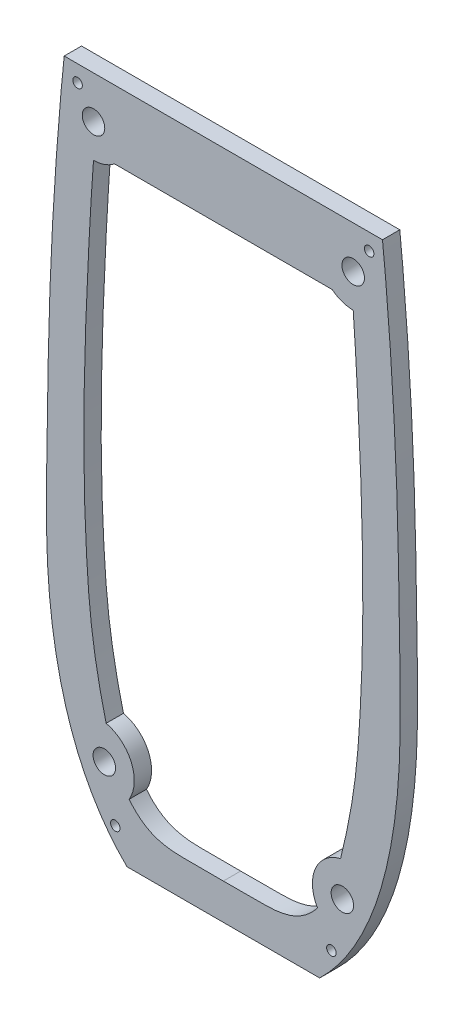
SolidWorks part; units mm, degrees
ref_plane "Front Plane" through (0, 0, 0) normal (0, 0, 1) x (1, 0, 0)
ref_plane "Top Plane" through (0, 0, 0) normal (0, 1, 0) x (1, 0, 0)
ref_plane "Right Plane" through (0, 0, 0) normal (1, 0, 0) x (0, 0, -1)
sketch "Sketch1" plane through (0, 0, 0) normal (0, 0, 1) x (1, 0, 0)
  line L5 (0, 5.6921) -> (0, 13.9608)
  line L6 (0, 5.6921) -> (-22.2594, 5.6921)
  line L7 (-36.7676, 160.6704) -> (0, 160.6704)
  line L8 (0, 160.6704) -> (0, 144.8979)
  line L9 (0, 144.8979) -> (-25.1616, 144.8979)
  circle A0 centre (-27.5, 24.0877) radius 2.6
  circle A1 centre (-30, 150.9111) radius 2.6
  ellipse E2 centre (-33.6879, 156.8491) end of major axis (-34.7879, 156.8491) minor radius 1.0993
  ellipse E6 centre (-24.9634, 12.5666) end of major axis (-26.0634, 12.5666) minor radius 1.0993
  ellipse E10 centre (-29.0357, 23.7592) end of major axis (-20.5773, 23.7592) minor radius 8.4532 (-21.7581, 19.4513) -> (-27.0802, 31.9834) ccw
  ellipse E11 centre (-30, 150.9111) end of major axis (-37.7209, 150.9111) minor radius 7.7162 (-30.0026, 143.1949) -> (-25.1616, 144.8979) ccw
  spline S3 degree 3 poles (-27.0802, 31.9834) (-28.7066, 38.3966) (-30.5155, 47.8152) (-32.4164, 73.4344) (-32.5527, 100.1202) (-30.5393, 136.0483) (-30.0026, 143.1949) knots 0.399897 0.399897 0.399897 0.399897 0.535865 0.58242 0.865441 0.989183 0.989183 0.989183 0.989183
  spline S4 degree 3 poles (0, 13.9608) (-10.8993, 13.9608) (-11.4872, 13.9593) (-16.2356, 14.8375) (-19.4228, 16.4556) (-21.7581, 19.4513) knots 0 0 0 0 0.128416 0.156586 0.281701 0.281701 0.281701 0.281701
  spline S5 degree 3 poles (-36.7676, 160.6704) (-37.0466, 158.6078) (-40.072, 127.3859) (-40.8032, 77.5361) (-41.3432, 45.3581) (-33.8942, 17.0373) (-22.2594, 5.6921) knots 0 0 0 0 0.322711 0.500185 0.698744 1 1 1 1
  point P18 (-27.5, 24.0877)
  point P19 (-30, 150.0782)
  point P20 (-30, 150.9111)
  point P21 (-30, 150.0782)
  point P56 (27.5, 23.2209)
  point P72 (30, 150.9111)
  dimension "D1" = 5.2
  dimension "D2" = 5.2
extrude "Boss-Extrude1" add sketch "Sketch1" along normal blind 4
mirror "Mirror1" about plane through (0, 160.6704, 4) normal (-1, 0, 0) of "Boss-Extrude1"
